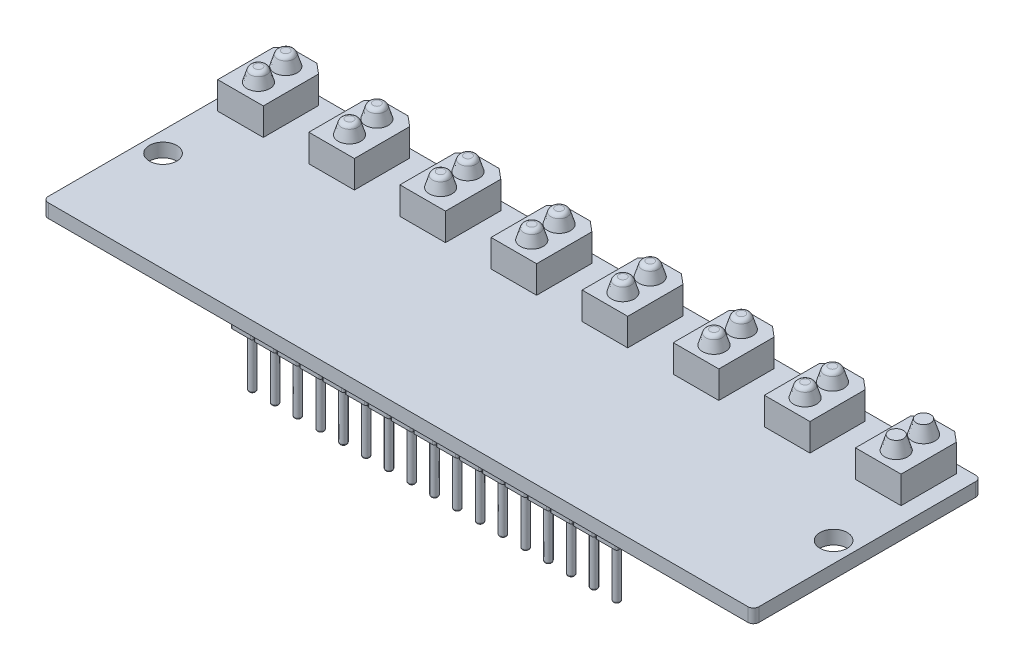
SolidWorks part; units mm, degrees
ref_plane "Front Plane" through (0, 0, 0) normal (0, 0, 1) x (1, 0, 0)
ref_plane "Top Plane" through (0, 0, 0) normal (0, 1, 0) x (1, 0, 0)
ref_plane "Right Plane" through (0, 0, 0) normal (1, 0, 0) x (0, 0, -1)
sketch "Sketch1" plane through (0, 0, 0) normal (0, 1, 0) x (1, 0, 0)
  line L1 (39, -12.5) -> (-39, -12.5)
  line L2 (39, -12.5) -> (39, 12.5)
  line L3 (39, 12.5) -> (-39, 12.5)
  line L4 (-39, -12.5) -> (-39, 12.5)
  line L5 (39, -12.5) -> (-39, 12.5) construction
  line L6 (39, 12.5) -> (-39, -12.5) construction
  point P0 (0, 0)
  dimension "D1" = 25
  dimension "D2" = 78
extrude "Boss-Extrude1" add sketch "Sketch1" along normal blind 1.5
fillet "Fillet1" radius 0.6 4 edges at (39, 0.75, 12.5) (39, 0.75, -12.5) (-39, 0.75, -12.5) (-39, 0.75, 12.5)
sketch "Sketch2" plane through (0, 1.5, 0) normal (0, 1, 0) x (1, 0, 0)
  line L0 (0, 0) -> (0, 12.5) construction
  line L1 (38.4, 12.5) -> (-38.4, 12.5) construction
  circle A0 centre (-36.8, -1.5) radius 1.5
  circle A1 centre (36.8, -1.5) radius 1.5
  dimension "D1" = 3
  dimension "D2" = 14
  dimension "D3" = 36.8
extrude "Cut-Extrude1" cut sketch "Sketch2" against normal blind 1.5
sketch "Sketch3" plane through (0, 1.5, 0) normal (0, 1, 0) x (1, 0, 0)
  line L0 (38.4, 12.5) -> (-38.4, 12.5) construction
  line L1 (-36.8668, 12.5) -> (-33.914, 12.5)
  line L2 (-37.8, 11.5668) -> (-37.8, 5.5)
  line L3 (-37.8, 5.5) -> (-32.8, 5.5)
  line L4 (-32.8, 11.5668) -> (-32.8, 5.5)
  line L5 (-37.4112, 11.9556) -> (-32.8, 5.5) construction
  line L6 (-37.8, 5.5) -> (-33.217, 11.9161) construction
  line L7 (-39, 11.9) -> (-39, -11.9) construction
  line L8 (-36.8668, 12.5) -> (-37.8, 11.5668)
  line L9 (-33.914, 12.5) -> (-32.8, 11.5668)
  line L10 (-22.8, 11.5668) -> (-22.8, 5.5)
  line L11 (-23.914, 12.5) -> (-22.8, 11.5668)
  line L12 (-26.8668, 12.5) -> (-23.914, 12.5)
  line L13 (-26.8668, 12.5) -> (-27.8, 11.5668)
  line L14 (-27.8, 11.5668) -> (-27.8, 5.5)
  line L15 (-27.8, 5.5) -> (-22.8, 5.5)
  line L16 (-12.8, 11.5668) -> (-12.8, 5.5)
  line L17 (-13.914, 12.5) -> (-12.8, 11.5668)
  line L18 (-16.8668, 12.5) -> (-13.914, 12.5)
  line L19 (-16.8668, 12.5) -> (-17.8, 11.5668)
  line L20 (-17.8, 11.5668) -> (-17.8, 5.5)
  line L21 (-17.8, 5.5) -> (-12.8, 5.5)
  line L22 (-2.8, 11.5668) -> (-2.8, 5.5)
  line L23 (-3.914, 12.5) -> (-2.8, 11.5668)
  line L24 (-6.8668, 12.5) -> (-3.914, 12.5)
  line L25 (-6.8668, 12.5) -> (-7.8, 11.5668)
  line L26 (-7.8, 11.5668) -> (-7.8, 5.5)
  line L27 (-7.8, 5.5) -> (-2.8, 5.5)
  line L28 (7.2, 11.5668) -> (7.2, 5.5)
  line L29 (6.086, 12.5) -> (7.2, 11.5668)
  line L30 (3.1332, 12.5) -> (6.086, 12.5)
  line L31 (3.1332, 12.5) -> (2.2, 11.5668)
  line L32 (2.2, 11.5668) -> (2.2, 5.5)
  line L33 (2.2, 5.5) -> (7.2, 5.5)
  line L34 (17.2, 11.5668) -> (17.2, 5.5)
  line L35 (16.086, 12.5) -> (17.2, 11.5668)
  line L36 (13.1332, 12.5) -> (16.086, 12.5)
  line L37 (13.1332, 12.5) -> (12.2, 11.5668)
  line L38 (12.2, 11.5668) -> (12.2, 5.5)
  line L39 (12.2, 5.5) -> (17.2, 5.5)
  line L40 (27.2, 11.5668) -> (27.2, 5.5)
  line L41 (26.086, 12.5) -> (27.2, 11.5668)
  line L42 (23.1332, 12.5) -> (26.086, 12.5)
  line L43 (23.1332, 12.5) -> (22.2, 11.5668)
  line L44 (22.2, 11.5668) -> (22.2, 5.5)
  line L45 (22.2, 5.5) -> (27.2, 5.5)
  line L46 (37.2, 11.5668) -> (37.2, 5.5)
  line L47 (36.086, 12.5) -> (37.2, 11.5668)
  line L48 (33.1332, 12.5) -> (36.086, 12.5)
  line L49 (33.1332, 12.5) -> (32.2, 11.5668)
  line L50 (32.2, 11.5668) -> (32.2, 5.5)
  line L51 (32.2, 5.5) -> (37.2, 5.5)
  point P0 (-35.3, 9)
  dimension "D1" = 5
  dimension "D2" = 7
  dimension "D3" = 0
  dimension "D4" = 1.2
  dimension "D5" = 8
extrude "Boss-Extrude2" add sketch "Sketch3" along normal blind 3
sketch "Sketch4" plane through (0, 4.5, 0) normal (0, 1, 0) x (1, 0, 0)
  line L0 (-37.8, 11.5668) -> (-37.8, 5.5) construction
  line L2 (-37.8, 5.5) -> (-32.8, 5.5) construction
  line L3 (-37.8, 5.5) -> (-32.8, 5.5) construction
  circle A0 centre (-35.33, 10.4996) radius 1.25
  circle A1 centre (-35.33, 7.5) radius 1.25
  circle A2 centre (-25.33, 10.4996) radius 1.25 construction
  circle A3 centre (-25.33, 7.5) radius 1.25 construction
  circle A4 centre (-15.33, 10.4996) radius 1.25 construction
  circle A5 centre (-15.33, 7.5) radius 1.25 construction
  circle A6 centre (-5.33, 10.4996) radius 1.25 construction
  circle A7 centre (-5.33, 7.5) radius 1.25 construction
  circle A8 centre (4.67, 10.4996) radius 1.25 construction
  circle A9 centre (4.67, 7.5) radius 1.25 construction
  circle A10 centre (14.67, 10.4996) radius 1.25 construction
  circle A11 centre (14.67, 7.5) radius 1.25 construction
  circle A12 centre (24.67, 10.4996) radius 1.25 construction
  circle A13 centre (24.67, 7.5) radius 1.25 construction
  circle A14 centre (34.67, 10.4996) radius 1.25 construction
  circle A15 centre (34.67, 7.5) radius 1.25 construction
  circle A16 centre (-25.33, 10.4996) radius 1.25
  circle A17 centre (-25.33, 7.5) radius 1.25
  circle A18 centre (-15.33, 10.4996) radius 1.25
  circle A19 centre (-15.33, 7.5) radius 1.25
  circle A20 centre (-5.33, 10.4996) radius 1.25
  circle A21 centre (-5.33, 7.5) radius 1.25
  circle A22 centre (4.67, 10.4996) radius 1.25
  circle A23 centre (4.67, 7.5) radius 1.25
  circle A24 centre (14.67, 10.4996) radius 1.25
  circle A25 centre (14.67, 7.5) radius 1.25
  circle A26 centre (24.67, 10.4996) radius 1.25
  circle A27 centre (24.67, 7.5) radius 1.25
  circle A28 centre (34.67, 10.4996) radius 1.25
  circle A29 centre (34.67, 7.5) radius 1.25
  dimension "D1" = 10
  dimension "D2" = 2.5
  dimension "D5" = 4.9996
  dimension "D6" = 2
  dimension "D3" = 2.47
  dimension "D7" = 8
  dimension "D8" = 8
extrude "Boss-Extrude7" add sketch "Sketch4" along normal blind 1.5 draft 17
fillet "Fillet4" radius 0.5 14 edges at (-35.33, 6, -9.7082) (-35.33, 6, -6.7086) (-25.33, 6, -9.7082) (-25.33, 6, -6.7086) (-15.33, 6, -9.7082) (-15.33, 6, -6.7086) (-5.33, 6, -9.7082) (-5.33, 6, -6.7086) (24.67, 6, -6.7086) (24.67, 6, -9.7082) (14.67, 6, -6.7086) (14.67, 6, -9.7082) (4.67, 6, -6.7086) (4.67, 6, -9.7082)
sketch "Sketch5" plane through (0, 0, 0) normal (0, -1, 0) x (1, 0, 0)
  line L0 (38.4, -12.5) -> (-38.4, -12.5) construction
  line L1 (-22.5, 10.9) -> (-20.1, 10.9)
  line L2 (-22.5, 10.9) -> (-22.5, 8.5)
  line L3 (-22.5, 8.5) -> (-20.1, 8.5)
  line L4 (-20.1, 10.9) -> (-20.1, 8.5)
  line L5 (-22.5, 10.9) -> (-20.1, 8.5) construction
  line L6 (-22.5, 8.5) -> (-20.1, 10.9) construction
  line L7 (-20, 10.9) -> (-20, 8.5)
  line L8 (-17.6, 10.9) -> (-17.6, 8.5)
  line L9 (-20, 8.5) -> (-17.6, 8.5)
  line L10 (-17.5, 10.9) -> (-17.5, 8.5)
  line L11 (-15.1, 10.9) -> (-15.1, 8.5)
  line L12 (-17.5, 8.5) -> (-15.1, 8.5)
  line L13 (-15, 10.9) -> (-15, 8.5)
  line L14 (-12.6, 10.9) -> (-12.6, 8.5)
  line L15 (-15, 8.5) -> (-12.6, 8.5)
  line L16 (-12.5, 10.9) -> (-12.5, 8.5)
  line L17 (-10.1, 10.9) -> (-10.1, 8.5)
  line L18 (-12.5, 8.5) -> (-10.1, 8.5)
  line L19 (-10, 10.9) -> (-10, 8.5)
  line L20 (-7.6, 10.9) -> (-7.6, 8.5)
  line L21 (-10, 8.5) -> (-7.6, 8.5)
  line L22 (-7.5, 10.9) -> (-7.5, 8.5)
  line L23 (-5.1, 10.9) -> (-5.1, 8.5)
  line L24 (-7.5, 8.5) -> (-5.1, 8.5)
  line L25 (-5, 10.9) -> (-5, 8.5)
  line L26 (-2.6, 10.9) -> (-2.6, 8.5)
  line L27 (-5, 8.5) -> (-2.6, 8.5)
  line L28 (-2.5, 10.9) -> (-2.5, 8.5)
  line L29 (-0.1, 10.9) -> (-0.1, 8.5)
  line L30 (-2.5, 8.5) -> (-0.1, 8.5)
  line L31 (0, 10.9) -> (0, 8.5)
  line L32 (2.4, 10.9) -> (2.4, 8.5)
  line L33 (0, 8.5) -> (2.4, 8.5)
  line L34 (2.5, 10.9) -> (2.5, 8.5)
  line L35 (4.9, 10.9) -> (4.9, 8.5)
  line L36 (2.5, 8.5) -> (4.9, 8.5)
  line L37 (5, 10.9) -> (5, 8.5)
  line L38 (7.4, 10.9) -> (7.4, 8.5)
  line L39 (5, 8.5) -> (7.4, 8.5)
  line L40 (7.5, 10.9) -> (7.5, 8.5)
  line L41 (9.9, 10.9) -> (9.9, 8.5)
  line L42 (7.5, 8.5) -> (9.9, 8.5)
  line L43 (10, 10.9) -> (10, 8.5)
  line L44 (12.4, 10.9) -> (12.4, 8.5)
  line L45 (10, 8.5) -> (12.4, 8.5)
  line L46 (12.5, 10.9) -> (12.5, 8.5)
  line L47 (14.9, 10.9) -> (14.9, 8.5)
  line L48 (12.5, 8.5) -> (14.9, 8.5)
  line L49 (15, 10.9) -> (15, 8.5)
  line L50 (17.4, 10.9) -> (17.4, 8.5)
  line L51 (15, 8.5) -> (17.4, 8.5)
  line L52 (17.5, 10.9) -> (17.5, 8.5)
  line L53 (19.9, 10.9) -> (19.9, 8.5)
  line L54 (17.5, 8.5) -> (19.9, 8.5)
  line L55 (20, 10.9) -> (20, 8.5)
  line L56 (22.4, 10.9) -> (22.4, 8.5)
  line L57 (20, 8.5) -> (22.4, 8.5)
  line L58 (-20, 10.9) -> (-20, 8.5)
  line L59 (-17.6, 10.9) -> (-17.6, 8.5)
  line L60 (-20, 8.5) -> (-17.6, 8.5)
  line L61 (-20, 10.9) -> (-17.6, 10.9)
  line L62 (-17.5, 10.9) -> (-17.5, 8.5)
  line L63 (-15.1, 10.9) -> (-15.1, 8.5)
  line L64 (-17.5, 8.5) -> (-15.1, 8.5)
  line L65 (-17.5, 10.9) -> (-15.1, 10.9)
  line L66 (-15, 10.9) -> (-15, 8.5)
  line L67 (-12.6, 10.9) -> (-12.6, 8.5)
  line L68 (-15, 8.5) -> (-12.6, 8.5)
  line L69 (-15, 10.9) -> (-12.6, 10.9)
  line L70 (-12.5, 10.9) -> (-12.5, 8.5)
  line L71 (-10.1, 10.9) -> (-10.1, 8.5)
  line L72 (-12.5, 8.5) -> (-10.1, 8.5)
  line L73 (-12.5, 10.9) -> (-10.1, 10.9)
  line L74 (-10, 10.9) -> (-10, 8.5)
  line L75 (-7.6, 10.9) -> (-7.6, 8.5)
  line L76 (-10, 8.5) -> (-7.6, 8.5)
  line L77 (-10, 10.9) -> (-7.6, 10.9)
  line L78 (-7.5, 10.9) -> (-7.5, 8.5)
  line L79 (-5.1, 10.9) -> (-5.1, 8.5)
  line L80 (-7.5, 8.5) -> (-5.1, 8.5)
  line L81 (-7.5, 10.9) -> (-5.1, 10.9)
  line L82 (-5, 10.9) -> (-5, 8.5)
  line L83 (-2.6, 10.9) -> (-2.6, 8.5)
  line L84 (-5, 8.5) -> (-2.6, 8.5)
  line L85 (-5, 10.9) -> (-2.6, 10.9)
  line L86 (-2.5, 10.9) -> (-2.5, 8.5)
  line L87 (-0.1, 10.9) -> (-0.1, 8.5)
  line L88 (-2.5, 8.5) -> (-0.1, 8.5)
  line L89 (-2.5, 10.9) -> (-0.1, 10.9)
  line L90 (0, 10.9) -> (0, 8.5)
  line L91 (2.4, 10.9) -> (2.4, 8.5)
  line L92 (0, 8.5) -> (2.4, 8.5)
  line L93 (0, 10.9) -> (2.4, 10.9)
  line L94 (2.5, 10.9) -> (2.5, 8.5)
  line L95 (4.9, 10.9) -> (4.9, 8.5)
  line L96 (2.5, 8.5) -> (4.9, 8.5)
  line L97 (2.5, 10.9) -> (4.9, 10.9)
  line L98 (5, 10.9) -> (5, 8.5)
  line L99 (7.4, 10.9) -> (7.4, 8.5)
  line L100 (5, 8.5) -> (7.4, 8.5)
  line L101 (5, 10.9) -> (7.4, 10.9)
  line L102 (7.5, 10.9) -> (7.5, 8.5)
  line L103 (9.9, 10.9) -> (9.9, 8.5)
  line L104 (7.5, 8.5) -> (9.9, 8.5)
  line L105 (7.5, 10.9) -> (9.9, 10.9)
  line L106 (10, 10.9) -> (10, 8.5)
  line L107 (12.4, 10.9) -> (12.4, 8.5)
  line L108 (10, 8.5) -> (12.4, 8.5)
  line L109 (10, 10.9) -> (12.4, 10.9)
  line L110 (12.5, 10.9) -> (12.5, 8.5)
  line L111 (14.9, 10.9) -> (14.9, 8.5)
  line L112 (12.5, 8.5) -> (14.9, 8.5)
  line L113 (12.5, 10.9) -> (14.9, 10.9)
  line L114 (15, 10.9) -> (15, 8.5)
  line L115 (17.4, 10.9) -> (17.4, 8.5)
  line L116 (15, 8.5) -> (17.4, 8.5)
  line L117 (15, 10.9) -> (17.4, 10.9)
  line L118 (17.5, 10.9) -> (17.5, 8.5)
  line L119 (19.9, 10.9) -> (19.9, 8.5)
  line L120 (17.5, 8.5) -> (19.9, 8.5)
  line L121 (17.5, 10.9) -> (19.9, 10.9)
  line L122 (20, 10.9) -> (20, 8.5)
  line L123 (22.4, 10.9) -> (22.4, 8.5)
  line L124 (20, 8.5) -> (22.4, 8.5)
  line L125 (20, 10.9) -> (22.4, 10.9)
  line L126 (-39, -11.9) -> (-39, 11.9) construction
  point P0 (-21.3, 9.7)
  dimension "D1" = 2.4
  dimension "D2" = 2.4
  dimension "D3" = 21
  dimension "D6" = 16.5
  dimension "D4" = 18
  dimension "D5" = 18
extrude "Boss-Extrude12" add sketch "Sketch5" along normal blind 2 contours L65 L10 L12 L11 | L69 L13 L15 L14 | L73 L16 L18 L17 | L77 L19 L21 L20 | L81 L22 L24 L23 | L61 L7 L9 L8 | L85 L25 L27 L26 | L89 L28 L30 L29 | L93 L31 L33 L32 | L97 L34 L36 L35 | L101 L37 L39 L38 | L105 L40 L42 L41 | L109 L43 L45 L44 | L113 L46 L48 L47 | L117 L49 L51 L50 | L121 L52 L54 L53 | L125 L55 L57 L56
sketch "Sketch6" plane through (0, -2, 0) normal (0, -1, 0) x (1, 0, 0)
  line L0 (-20, 8.5) -> (-17.6, 8.5) construction
  line L1 (-20, 10.9) -> (-17.6, 10.9) construction
  circle A0 centre (-18.8, 9.7) radius 0.375
  circle A1 centre (-16.3, 9.7) radius 0.375
  circle A2 centre (-13.8, 9.7) radius 0.375
  circle A3 centre (-11.3, 9.7) radius 0.375
  circle A4 centre (-8.8, 9.7) radius 0.375
  circle A5 centre (-6.3, 9.7) radius 0.375
  circle A6 centre (-3.8, 9.7) radius 0.375
  circle A7 centre (-1.3, 9.7) radius 0.375
  circle A8 centre (1.2, 9.7) radius 0.375
  circle A9 centre (3.7, 9.7) radius 0.375
  circle A10 centre (6.2, 9.7) radius 0.375
  circle A11 centre (8.7, 9.7) radius 0.375
  circle A12 centre (11.2, 9.7) radius 0.375
  circle A13 centre (13.7, 9.7) radius 0.375
  circle A14 centre (16.2, 9.7) radius 0.375
  circle A15 centre (18.7, 9.7) radius 0.375
  circle A16 centre (21.2, 9.7) radius 0.375
  point P4 (-18.8, 10.9)
  dimension "D1" = 1.2
  dimension "D2" = 1.2
  dimension "D3" = 0.75
  dimension "D4" = 17
extrude "Boss-Extrude13" add sketch "Sketch6" along normal blind 6
fillet "Fillet5" radius 0.2 4 edges at (-17.6, -1, 10.9) (-17.6, -1, 8.5) (-20, -1, 8.5) (-20, -1, 10.9)
fillet "Fillet7" radius 0.2 64 edges at (22.4, -1, 8.5) (20, -1, 8.5) (19.9, -1, 8.5) (17.5, -1, 8.5) (17.4, -1, 8.5) (15, -1, 8.5) (14.9, -1, 8.5) (12.5, -1, 8.5) (12.4, -1, 8.5) (10, -1, 8.5) (9.9, -1, 8.5) (7.5, -1, 8.5) (7.4, -1, 8.5) (5, -1, 8.5) (4.9, -1, 8.5) (2.5, -1, 8.5) (2.4, -1, 8.5) (0, -1, 8.5) (-0.1, -1, 8.5) (-2.5, -1, 8.5) (-2.6, -1, 8.5) (-5, -1, 8.5) (-5.1, -1, 8.5) (-7.5, -1, 8.5) (-7.6, -1, 8.5) (-10, -1, 8.5) (-10.1, -1, 8.5) (-12.5, -1, 8.5) (-12.6, -1, 8.5) (-15, -1, 8.5) (-15.1, -1, 8.5) (-17.5, -1, 8.5) (22.4, -1, 10.9) (20, -1, 10.9) (19.9, -1, 10.9) (17.5, -1, 10.9) (17.4, -1, 10.9) (15, -1, 10.9) (14.9, -1, 10.9) (12.5, -1, 10.9) (12.4, -1, 10.9) (10, -1, 10.9) (9.9, -1, 10.9) (7.5, -1, 10.9) (7.4, -1, 10.9) (5, -1, 10.9) (4.9, -1, 10.9) (2.5, -1, 10.9) (2.4, -1, 10.9) (0, -1, 10.9) (-0.1, -1, 10.9) (-2.5, -1, 10.9) (-2.6, -1, 10.9) (-5, -1, 10.9) (-5.1, -1, 10.9) (-7.5, -1, 10.9) (-7.6, -1, 10.9) (-10, -1, 10.9) (-10.1, -1, 10.9) (-12.5, -1, 10.9) (-12.6, -1, 10.9) (-15, -1, 10.9) (-15.1, -1, 10.9) (-17.5, -1, 10.9)
fillet "Fillet8" radius 0.2 17 edges at (21.2, -8, 9.325) (18.7, -8, 9.325) (16.2, -8, 9.325) (13.7, -8, 9.325) (11.2, -8, 9.325) (8.7, -8, 9.325) (6.2, -8, 9.325) (3.7, -8, 9.325) (1.2, -8, 9.325) (-1.3, -8, 9.325) (-3.8, -8, 9.325) (-6.3, -8, 9.325) (-8.8, -8, 9.325) (-11.3, -8, 9.325) (-13.8, -8, 9.325) (-16.3, -8, 9.325) (-18.8, -8, 9.325)
